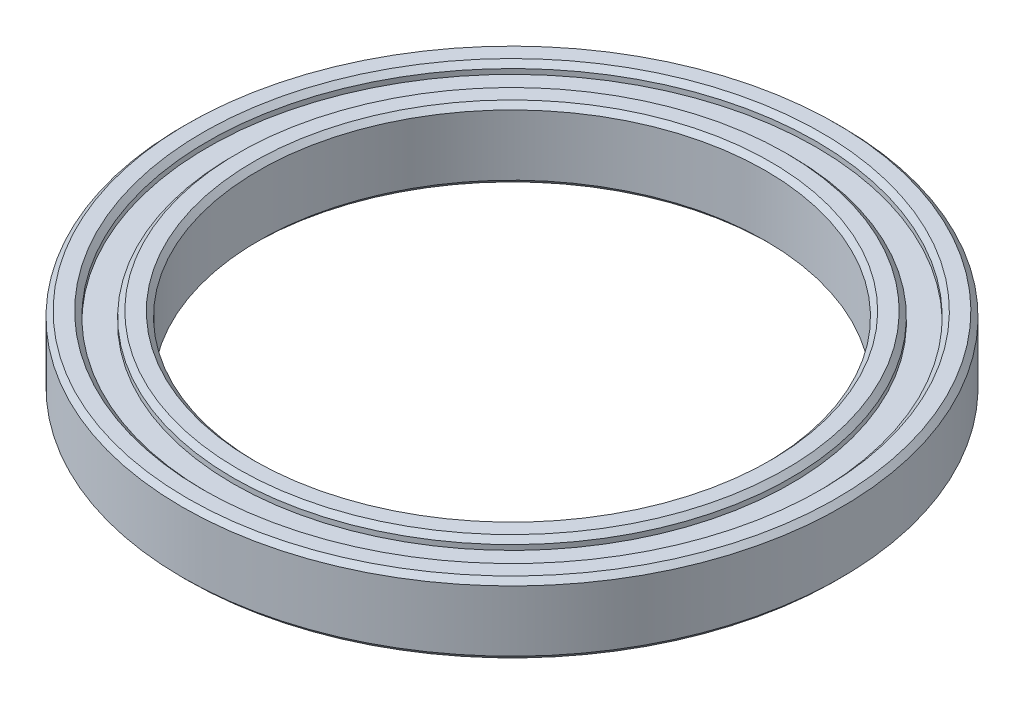
SolidWorks part; units mm, degrees
ref_plane "Front Plane" through (0, 0, 0) normal (0, 0, 1) x (1, 0, 0)
ref_plane "Top Plane" through (0, 0, 0) normal (0, 1, 0) x (1, 0, 0)
ref_plane "Right Plane" through (0, 0, 0) normal (1, 0, 0) x (0, 0, -1)
sketch "Sketch1" plane through (0, 0, 0) normal (0, 1, 0) x (1, 0, 0)
  circle A0 centre (0, 0) radius 25
  circle A1 centre (0, 0) radius 32.5
  dimension "D1" = 50
  dimension "D2" = 65
extrude "Boss-Extrude1" add sketch "Sketch1" along normal blind 7
sketch "Sketch2" plane through (0, 7, 0) normal (0, 1, 0) x (1, 0, 0)
  circle A0 centre (0, 0) radius 27.5
  circle A1 centre (0, 0) radius 30
  dimension "D1" = 60
  dimension "D2" = 55
extrude "Cut-Extrude1" cut sketch "Sketch2" against normal blind 1
sketch "Sketch3" plane through (0, 0, 0) normal (0, -1, 0) x (1, 0, 0)
  circle A0 centre (0, 0) radius 27.5
  circle A1 centre (0, 0) radius 30
  dimension "D1" = 60
  dimension "D2" = 55
extrude "Cut-Extrude2" cut sketch "Sketch3" against normal blind 1
chamfer "Chamfer1" distance 0.5 angle 45 8 edges at (0, 0, -27.5) (0, 0, 25) (0, 0, 32.5) (0, 0, -30) (0, 7, 32.5) (0, 7, 30) (0, 7, 27.5) (0, 7, 25)
